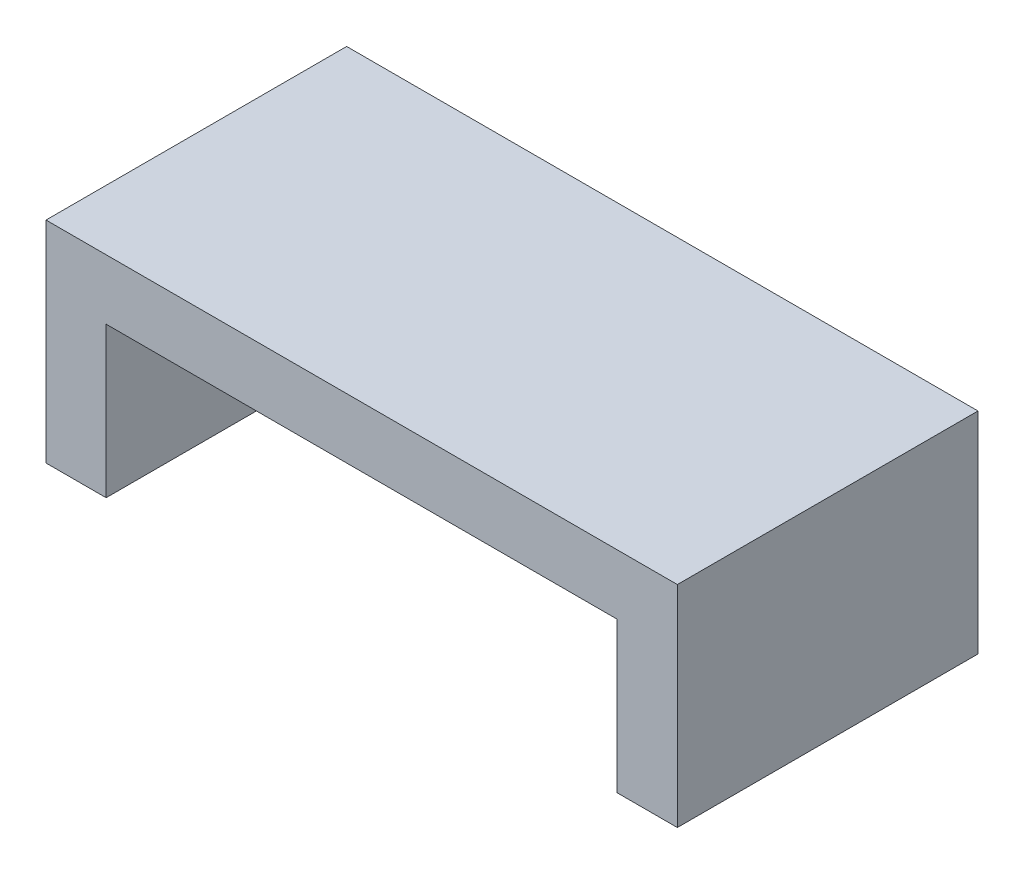
SolidWorks part; units mm, degrees
ref_plane "Front Plane" through (0, 0, 0) normal (0, 0, 1) x (1, 0, 0)
ref_plane "Top Plane" through (0, 0, 0) normal (0, 1, 0) x (1, 0, 0)
ref_plane "Right Plane" through (0, 0, 0) normal (1, 0, 0) x (0, 0, -1)
sketch "Sketch1" plane through (0, 0, 0) normal (0, 1, 0) x (1, 0, 0)
  line L1 (-7.7401, 6.1198) -> (13.2599, 6.1198)
  line L2 (-7.7401, 6.1198) -> (-7.7401, -3.8802)
  line L3 (-7.7401, -3.8802) -> (13.2599, -3.8802)
  line L4 (13.2599, 6.1198) -> (13.2599, -3.8802)
  dimension "D1" = 21
  dimension "D2" = 10
extrude "Boss-Extrude1" add sketch "Sketch1" along normal blind 7
sketch "Sketch2" plane through (0, 0, 3.8802) normal (0, 0, 1) x (1, 0, 0)
  line L0 (-7.7401, 0) -> (13.2599, 0) construction
  line L1 (-5.7401, 5) -> (11.2599, 5)
  line L2 (-5.7401, 5) -> (-5.7401, 0)
  line L3 (-5.7401, 0) -> (11.2599, 0)
  line L4 (11.2599, 5) -> (11.2599, 0)
  line L5 (-7.7401, 7) -> (-7.7401, 0) construction
  line L6 (-7.7401, 7) -> (13.2599, 7) construction
  line L7 (13.2599, 7) -> (13.2599, 0) construction
  dimension "D1" = 2
  dimension "D2" = 2
  dimension "D3" = 2
extrude "Cut-Extrude1" cut sketch "Sketch2" against normal up to surface (10 mm away) up to face at (2.7599, 3.5, -6.1198)
